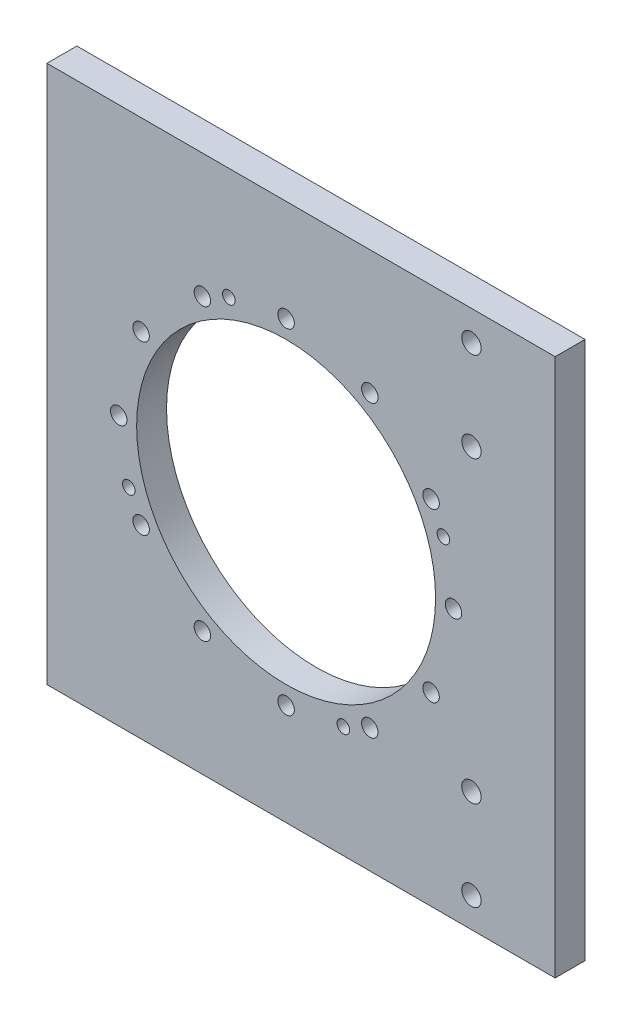
SolidWorks part; units mm, degrees
material "6061-T6 (SS)"
ref_plane "前视基准面" through (0, 0, 0) normal (0, 0, 1) x (1, 0, 0)
ref_plane "上视基准面" through (0, 0, 0) normal (0, 1, 0) x (1, 0, 0)
ref_plane "右视基准面" through (0, 0, 0) normal (1, 0, 0) x (0, 0, -1)
other "Configuration Table"
sketch "草图1" plane through (0, 0, 0) normal (0, 0, 1) x (1, 0, 0)
  line L0 (-80, -90) -> (90, -90)
  line L1 (90, -90) -> (90, 90)
  line L2 (90, 90) -> (-80, 90)
  line L3 (-80, 90) -> (-80, -90)
extrude "凸台-拉伸1" add sketch "草图1" along normal blind 10
sketch "草图2" plane through (0, 0, 0) normal (0, 0, -1) x (-1, 0, 0)
  circle A0 centre (0, 0) radius 50
  circle A1 centre (-56, 0) radius 2.75
  circle A2 centre (-48.4974, 28) radius 2.75
  circle A3 centre (-28, 48.4974) radius 2.75
  circle A4 centre (0, 56) radius 2.75
  circle A5 centre (28, 48.4974) radius 2.75
  circle A6 centre (48.4974, 28) radius 2.75
  circle A7 centre (56, 0) radius 2.75
  circle A8 centre (48.4974, -28) radius 2.75
  circle A9 centre (28, -48.4974) radius 2.75
  circle A10 centre (0, -56) radius 2.75
  circle A11 centre (-28, -48.4974) radius 2.75
  circle A12 centre (-48.4974, -28) radius 2.75
  circle A13 centre (-52.6228, 19.1531) radius 2.1
  circle A14 centre (19.1531, 52.6228) radius 2.1
  circle A15 centre (52.6228, -19.1531) radius 2.1
  circle A16 centre (-19.1531, -52.6228) radius 2.1
  circle A17 centre (-62, -80) radius 3.25
  circle A18 centre (-62, -50) radius 3.25
  circle A19 centre (-62, 50) radius 3.25
  circle A20 centre (-62, 80) radius 3.25
extrude "切除-拉伸1" cut sketch "草图2" against normal blind 11
